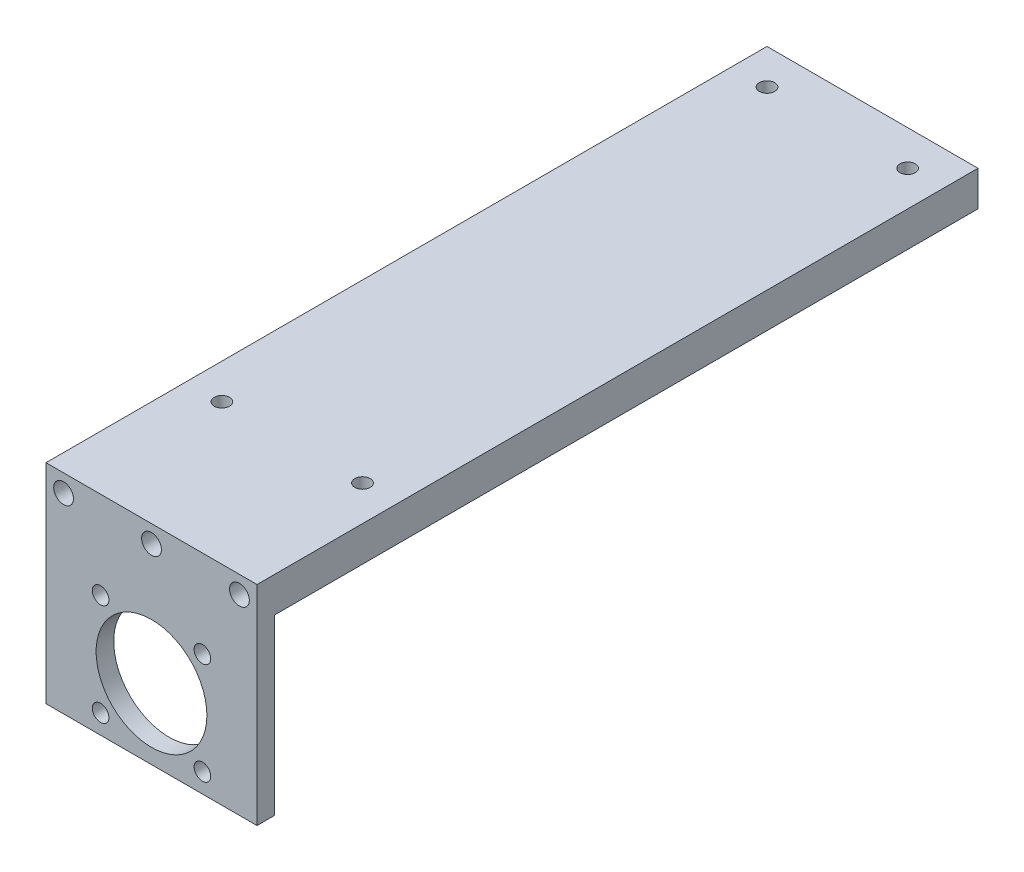
SolidWorks part; units mm, degrees
ref_plane "Front Plane" through (0, 0, 0) normal (0, 0, 1) x (1, 0, 0)
ref_plane "Top Plane" through (0, 0, 0) normal (0, 1, 0) x (1, 0, 0)
ref_plane "Right Plane" through (0, 0, 0) normal (1, 0, 0) x (0, 0, -1)
sketch "Sketch1" plane through (0, 0, 0) normal (0, 0, 1) x (1, 0, 0)
  line L9 (19.05, 24.9936) -> (0, 0) construction
  line L10 (19.05, 24.9936) -> (-19.05, 24.9936)
  line L11 (19.05, 24.9936) -> (19.05, -12.7)
  line L12 (9.1924, 9.1924) -> (-9.1924, 9.1924) construction
  line L13 (9.1924, 9.1924) -> (9.1924, -9.1924) construction
  line L14 (9.1924, -9.1924) -> (-9.1924, -9.1924) construction
  line L15 (-9.1924, 9.1924) -> (-9.1924, -9.1924) construction
  line L16 (9.1924, 9.1924) -> (-9.1924, -9.1924) construction
  line L17 (9.1924, -9.1924) -> (-9.1924, 9.1924) construction
  line L18 (19.05, -12.7) -> (-19.05, -12.7)
  line L19 (-19.05, 24.9936) -> (-19.05, -12.7)
  line L20 (0, 0) -> (-19.05, 24.9936) construction
  line L21 (15.875, 21.8186) -> (0, 21.8186) construction
  line L22 (0, 21.8186) -> (-15.875, 21.8186) construction
  line L23 (0, 21.8186) -> (0, 24.9936) construction
  circle A0 centre (0, 0) radius 10
  circle A1 centre (-9.1924, 9.1924) radius 1.5
  circle A2 centre (9.1924, 9.1924) radius 1.5
  circle A3 centre (9.1924, -9.1924) radius 1.5
  circle A4 centre (-9.1924, -9.1924) radius 1.5
  circle A5 centre (15.875, 21.8186) radius 1.7859
  circle A6 centre (0, 21.8186) radius 1.7859
  circle A7 centre (-15.875, 21.8186) radius 1.7859
  dimension "D5" = 20
  dimension "D7" = 3
  dimension "D8" = 3.175
  dimension "D9" = 3.5719
  dimension "D1" = 24.9936
  dimension "D2" = 38.1
  dimension "D3" = 12.7
  dimension "D4" = 3.175
  dimension "D6" = 26
extrude "Boss-Extrude1" add sketch "Sketch1" along normal blind 3.175
sketch "Sketch2" plane through (0, 0, 0) normal (0, 0, -1) x (-1, 0, 0)
  line L0 (19.05, 24.9936) -> (19.05, -12.7) construction
  line L1 (-19.05, 24.9936) -> (19.05, 24.9936)
  line L2 (-19.05, 24.9936) -> (-19.05, 18.6436)
  line L3 (-19.05, 18.6436) -> (19.05, 18.6436)
  line L4 (19.05, 24.9936) -> (19.05, 18.6436)
  dimension "D1" = 6.35
extrude "Boss-Extrude2" add sketch "Sketch2" along normal blind 127
sketch "Sketch3" plane through (0, 24.9936, 0) normal (0, 1, 0) x (1, 0, 0)
  line L0 (0, 120.65) -> (0, 127) construction
  line L1 (-12.7, 120.65) -> (12.7, 120.65) construction
  line L2 (-12.7, 120.65) -> (-12.7, 22.225) construction
  line L3 (-12.7, 22.225) -> (12.7, 22.225) construction
  line L4 (12.7, 120.65) -> (12.7, 22.225) construction
  line L5 (-19.05, 127) -> (19.05, 127) construction
  line L6 (19.05, -3.175) -> (-19.05, -3.175) construction
  line L7 (-19.05, -3.175) -> (-19.05, 127) construction
  circle A0 centre (-12.7, 120.65) radius 1.3891
  circle A1 centre (12.7, 120.65) radius 1.3891
  circle A2 centre (-12.7, 22.225) radius 1.3891
  circle A3 centre (12.7, 22.225) radius 1.3891
  dimension "D1" = 2.7781
  dimension "D2" = 6.35
  dimension "D3" = 25.4
  dimension "D4" = 6.35
extrude "Cut-Extrude1" cut sketch "Sketch3" against normal up to next
